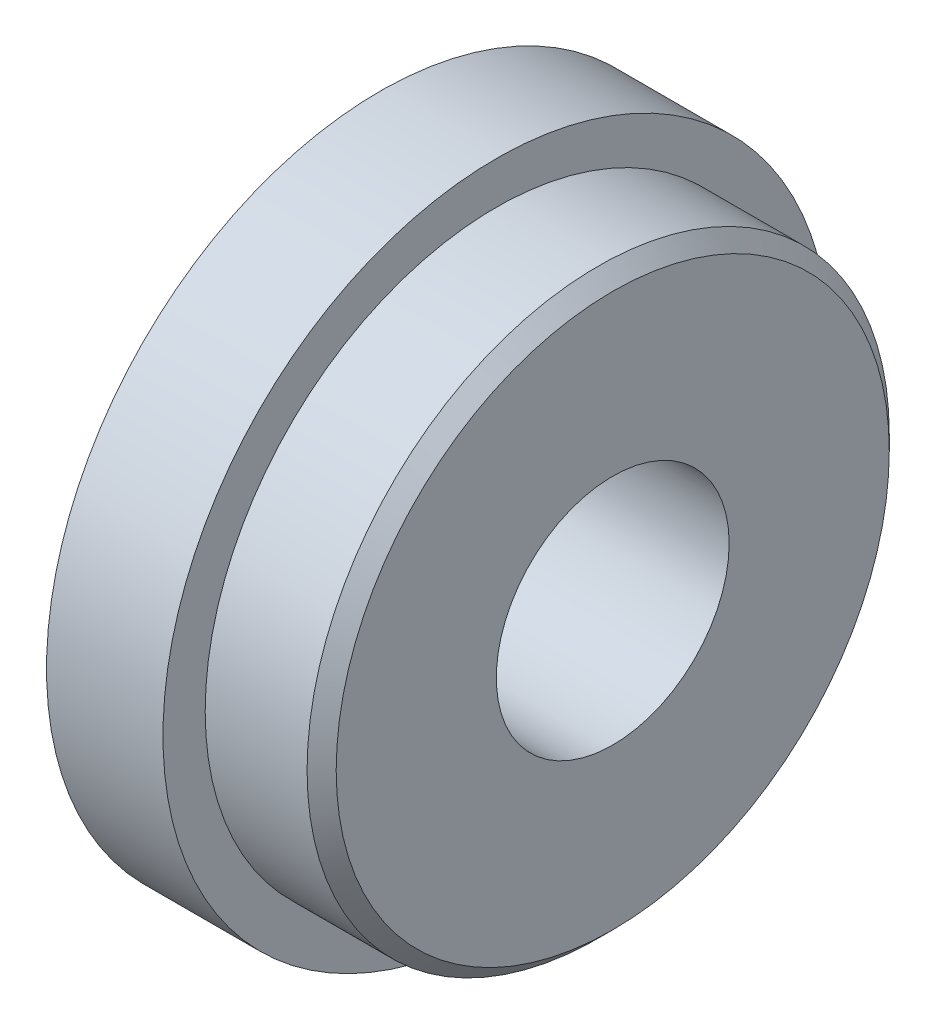
SolidWorks part; units mm, degrees
ref_plane "Front Plane" through (0, 0, 0) normal (0, 0, 1) x (1, 0, 0)
ref_plane "Top Plane" through (0, 0, 0) normal (0, 1, 0) x (1, 0, 0)
ref_plane "Right Plane" through (0, 0, 0) normal (1, 0, 0) x (0, 0, -1)
sketch "Sketch1" plane through (0, 0, 0) normal (1, 0, 0) x (0, 0, -1)
  circle A0 centre (0, 0) radius 11.45
  dimension "D1" = 22.9
extrude "Boss-Extrude1" add sketch "Sketch1" along normal blind 4
sketch "Sketch2" plane through (4, 0, 0) normal (1, 0, 0) x (0, 0, -1)
  circle A0 centre (0, 0) radius 10
  dimension "D1" = 20
extrude "Boss-Extrude2" add sketch "Sketch2" along normal blind 4
sketch "Sketch3" plane through (8, 0, 0) normal (1, 0, 0) x (0, 0, -1)
  circle A0 centre (0, 0) radius 4
  dimension "D1" = 8
extrude "Cut-Extrude1" cut sketch "Sketch3" against normal blind 8
chamfer "Chamfer1" distance 0.5 angle 45 2 edges at (8, 0, -10) (0, 0, -4)
